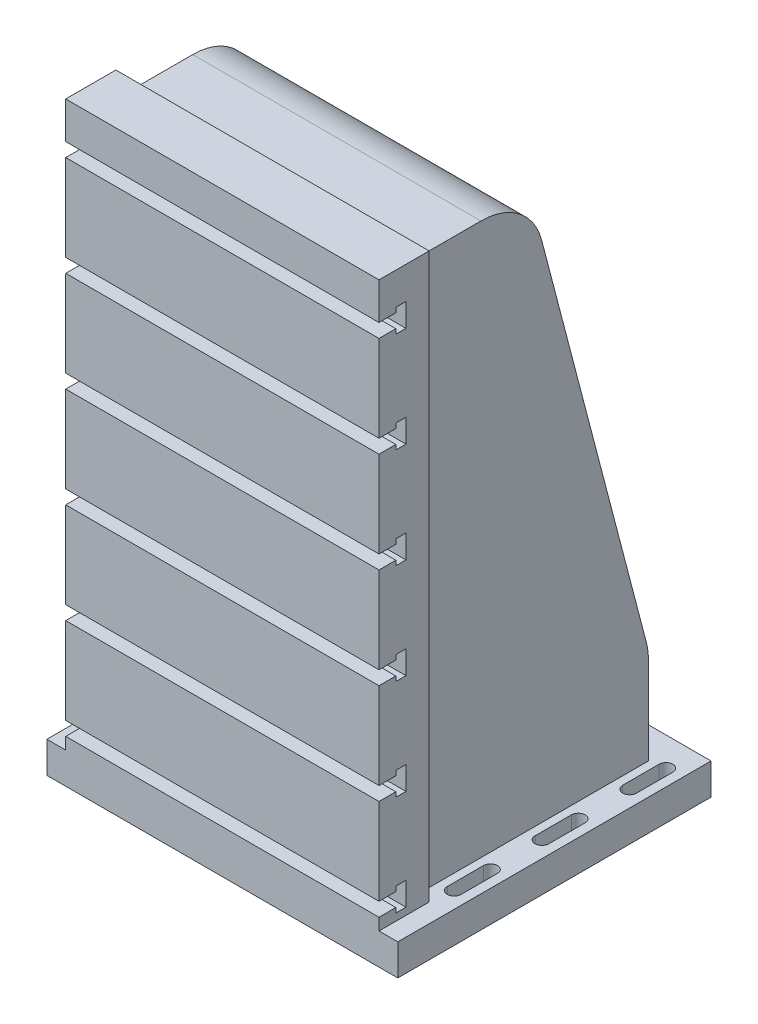
SolidWorks part; units mm, degrees
ref_plane "Front Plane" through (0, 0, 0) normal (0, 0, 1) x (1, 0, 0)
ref_plane "Top Plane" through (0, 0, 0) normal (0, 1, 0) x (1, 0, 0)
ref_plane "Right Plane" through (0, 0, 0) normal (1, 0, 0) x (0, 0, -1)
sketch "Sketch4" plane through (0, 0, 0) normal (1, 0, 0) x (0, 0, -1)
  line L0 (0, 0) -> (0, 950)
  line L5 (500, 0) -> (0, 0)
  line L6 (500, 50) -> (500, 0)
  line L7 (279.5237, 855.2806) -> (446.7517, 215.2806)
  line L8 (0, 950) -> (80, 950)
  line L9 (500, 50) -> (450, 50)
  line L10 (450, 50) -> (450, 190)
  line L11 (80, 950) -> (80, 930)
  line L12 (80, 930) -> (182.772, 930)
  arc A1 (450, 190) -> (446.7517, 215.2806) centre (350, 190) ccw
  arc A2 (182.772, 930) -> (279.5237, 855.2806) centre (182.772, 830) cw
  point P10 (254.7741, 950)
  point P19 (260, 930)
  dimension "D6" = 80
  dimension "D9" = 100
  dimension "D1" = 950
  dimension "D2" = 450
  dimension "D3" = 500
  dimension "D4" = 50
  dimension "D5" = 260
  dimension "D7" = 140
  dimension "D8" = 20
extrude "Boss-Extrude1" add sketch "Sketch4" along normal mid plane 560
ref_plane "Plane1" through (0, 50, 0) normal (0, 1, 0) x (1, 0, 0)
sketch "Sketch9" plane through (0, 50, 0) normal (0, 1, 0) x (1, 0, 0)
  line L1 (-230, 80) -> (-250, 80)
  line L2 (-230, 80) -> (-230, 560)
  line L3 (-230, 560) -> (-330, 560)
  line L4 (-330, -10) -> (-330, 560)
  line L5 (-280, 446.7517) -> (-280, 279.5237) construction
  line L6 (-250, 80) -> (-250, -10)
  line L7 (-250, -10) -> (-330, -10)
  line L8 (280, 0) -> (-280, 0) construction
  line L10 (-280, 80) -> (-280, 0) construction
  dimension "D1" = 10
  dimension "D2" = 50
  dimension "D3" = 100
  dimension "D4" = 80
  dimension "D5" = 30
  dimension "D6" = 570
extrude "Cut-Extrude2" cut sketch "Sketch9" along normal up to next
sketch "Sketch8"
sketch_block_instance "Block2-1"
sketch_block "Block2" parameters "D1"=37.2, "D2"=22, "D3"=26.9, "D4"=43
sketch "Sketch10" plane through (0, 0, 0) normal (0, -1, 0) x (1, 0, 0)
  line L0 (-254, -116) -> (-254, -174) construction
  line L1 (-243, -116) -> (-243, -174)
  line L2 (-265, -116) -> (-265, -174)
  line L3 (280, 0) -> (-280, 0) construction
  line L4 (-280, 0) -> (-280, -500) construction
  arc A0 (-243, -116) -> (-265, -116) centre (-254, -116) ccw
  arc A1 (-265, -174) -> (-243, -174) centre (-254, -174) ccw
  point P2 (-254, -145)
  point P7 (-254, -105)
  point P10 (-254, -185)
  dimension "D1" = 22
  dimension "D2" = 105
  dimension "D3" = 185
  dimension "D4" = 15
extrude "Cut-Extrude3" cut sketch "Sketch10" against normal up to next
pattern_linear "LPattern2" count 3 spacing 140 along (0, 0, -1) of "Cut-Extrude3"
sketch "Sketch6" plane through (280, 0, 0) normal (1, 0, 0) x (0, 0, -1)
  line L0 (0, 0) -> (500, 0) construction
  line L9 (0, -130.0402) -> (0, 14.2527) construction
  line B0 (0, 69) -> (0, 91)
  line B1 (0, 91) -> (26.9, 91)
  line B2 (26.9, 91) -> (26.9, 98.6)
  line B3 (26.9, 98.6) -> (43, 98.6)
  line B4 (43, 98.6) -> (43, 61.4)
  line B5 (43, 61.4) -> (26.9, 61.4)
  line B6 (26.9, 61.4) -> (26.9, 69)
  line B7 (26.9, 69) -> (0, 69)
  line B8 (0, 80) -> (43, 80) construction
  dimension "D1" = 80
sketch_block_instance "Block2-3"
extrude "Cut-Extrude1" cut sketch "Sketch6" against normal up to next
pattern_linear "LPattern1" count 6 spacing 160 along (0, 1, 0) of "Cut-Extrude1"
mirror "Mirror1" about plane through (0, 0, 0) normal (1, 0, 0) of "LPattern2", "Cut-Extrude2", "Cut-Extrude3"
